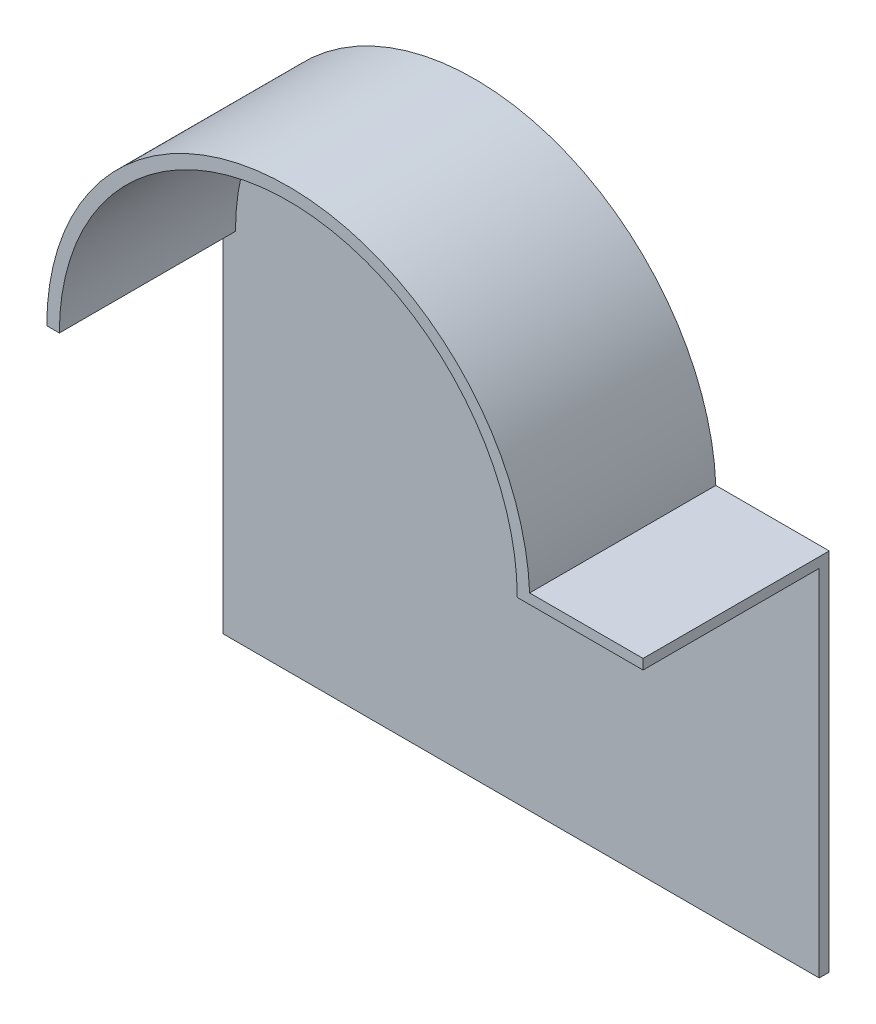
SolidWorks part; units mm, degrees
ref_plane "Plan de face" through (0, 0, 0) normal (0, 0, 1) x (1, 0, 0)
ref_plane "Plan de dessus" through (0, 0, 0) normal (0, 1, 0) x (1, 0, 0)
ref_plane "Plan de droite" through (0, 0, 0) normal (1, 0, 0) x (0, 0, -1)
sketch "Esquisse1" plane through (0, 0, 0) normal (0, 0, 1) x (1, 0, 0)
  line L4 (-48, 0) -> (-48, -68)
  line L5 (68, 0) -> (48, 0)
  line L7 (68, 0) -> (70.5, 0)
  line L10 (70.5, 0) -> (70.5, -68)
  line L12 (-48, -68) -> (-48, -70.5)
  line L13 (-48, -70.5) -> (70.5, -70.5)
  line L14 (70.5, -68) -> (70.5, -70.5)
  arc A1 (-48, 0) -> (48, 0) centre (0, 0) cw
  dimension "D1" = 20
  dimension "D2" = 48
  dimension "D5" = 68
  dimension "D6" = 2.5
  dimension "D7" = 2.5
sketch "Esquisse2" plane through (0, 0, 0) normal (0, 0, 1) x (1, 0, 0)
  line L1 (-68, 0) -> (-48, 0)
  line L2 (-68, 0) -> (-68, -68)
  line L3 (-68, -68) -> (48, -68)
  line L4 (48, 0) -> (48, -68)
  arc A0 (48, 0) -> (-48, 0) centre (0, 0) ccw
extrude "Boss.-Extru.1" add sketch "Esquisse1" along normal blind 2
sketch "Esquisse3" plane through (0, 0, 2) normal (0, 0, 1) x (1, 0, 0)
  line L9 (-45.5, 0) -> (-48, 0)
  line L12 (45.5, 0) -> (48, 0)
  arc A0 (45.5, 0) -> (-45.5, 0) centre (0, 0) ccw
  arc A1 (48, 0) -> (-48, 0) centre (0, 0) ccw
extrude "Boss.-Extru.2" add sketch "Esquisse3" along normal blind 35
sketch "Esquisse4" plane through (70.5, 0, 0) normal (1, 0, 0) x (0, 0, -1)
  line L0 (-37, 48) -> (-37, 0) construction
  line L1 (0, 0) -> (-37, 0)
  line L2 (0, 0) -> (0, 2)
  line L3 (0, 2) -> (-37, 2)
  line L4 (-37, 0) -> (-37, 2)
  dimension "D1" = 2
extrude "Boss.-Extru.3" add sketch "Esquisse4" against normal up to surface (22.5 mm away)
